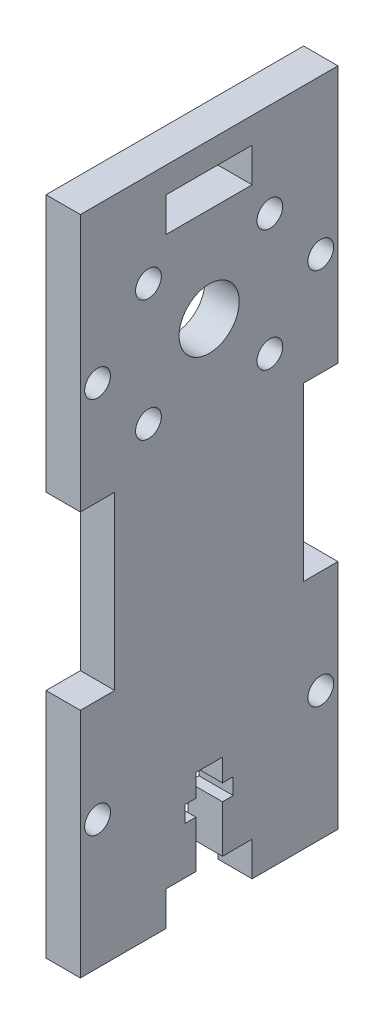
SolidWorks part; units mm, degrees
ref_plane "Front Plane" through (0, 0, 0) normal (0, 0, 1) x (1, 0, 0)
ref_plane "Top Plane" through (0, 0, 0) normal (0, 1, 0) x (1, 0, 0)
ref_plane "Right Plane" through (0, 0, 0) normal (1, 0, 0) x (0, 0, -1)
sketch "Sketch1" plane through (0, 0, 0) normal (1, 0, 0) x (0, 0, -1)
  line L0 (20, 74) -> (30, 74)
  line L1 (0, 0) -> (10, 0)
  line L2 (0, 0) -> (0, 74)
  line L3 (0, 74) -> (10, 74)
  line L4 (30, 0) -> (30, 74)
  line L6 (10, 74) -> (10, 70)
  line L7 (10, 70) -> (20, 70)
  line L8 (20, 74) -> (20, 70)
  line L10 (10, 0) -> (10, 4)
  line L11 (10, 4) -> (20, 4)
  line L12 (20, 0) -> (20, 4)
  line L13 (20, 0) -> (30, 0)
  line L14 (2, 74) -> (2, 0) construction
  line L15 (28, 74) -> (28, 0) construction
  line L16 (0, 37) -> (30, 37) construction
  line L18 (0, 47) -> (4, 47)
  line L19 (0, 47) -> (0, 27)
  line L20 (0, 27) -> (4, 27)
  line L21 (4, 47) -> (4, 27)
  line L22 (30, 27) -> (26, 27)
  line L23 (30, 27) -> (30, 47)
  line L24 (30, 47) -> (26, 47)
  line L25 (26, 27) -> (26, 47)
  circle A0 centre (2, 59) radius 1.5
  circle A1 centre (2, 15) radius 1.5
  circle A2 centre (28, 59) radius 1.5
  circle A3 centre (28, 15) radius 1.5
  dimension "D10" = 3
  dimension "D11" = 3
  dimension "D15" = 3
  dimension "D16" = 3
  dimension "D18" = 15
  dimension "D1" = 74
  dimension "D2" = 30
  dimension "D3" = 10
  dimension "D4" = 10
  dimension "D5" = 4
  dimension "D6" = 10
  dimension "D7" = 10
  dimension "D8" = 4
  dimension "D9" = 2
  dimension "D12" = 15
  dimension "D13" = 15
  dimension "D14" = 2
  dimension "D17" = 15
  dimension "D19" = 4
  dimension "D20" = 4
  dimension "D21" = 20
  dimension "D22" = 20
  dimension "D23" = 10
  dimension "D24" = 10
extrude "Boss-Extrude1" add sketch "Sketch1" along normal blind 4 contours L22 L25 L24 L4 L0 L8 L7 L6 L3 L2 L18 L21 L20 L1 L10 L11 L12 L13 A3 A2 A1 A0
sketch "Sketch2" plane through (4, 0, 0) normal (1, 0, 0) x (0, 0, -1)
  line L0 (20, 74) -> (30, 74) construction
  line L1 (0, 47) -> (0, 74) construction
  line L2 (15, 59) -> (5.4359, 59) construction
  line L3 (5.4359, 59) -> (15, 59) construction
  line L4 (15, 59) -> (3.0427, 70.9573) construction
  circle A0 centre (15, 59) radius 3.5
  circle A1 centre (7.9289, 66.0711) radius 1.5
  circle A2 centre (22.0711, 66.0711) radius 1.5
  circle A3 centre (22.0711, 51.9289) radius 1.5
  circle A4 centre (7.9289, 51.9289) radius 1.5
  point P19 (15, 59)
  dimension "D1" = 7
  dimension "D5" = 3
  dimension "D2" = 15
  dimension "D3" = 15
  dimension "D4" = 45
  dimension "D6" = 10
  dimension "D7" = 4
extrude "Cut-Extrude1" cut sketch "Sketch2" against normal blind 4
sketch "Sketch3" plane through (0, 74, 0) normal (0, 1, 0) x (1, 0, 0)
  line L1 (4, 0) -> (0, 0)
  line L2 (4, 0) -> (4, 30)
  line L3 (4, 30) -> (0, 30)
  line L4 (0, 0) -> (0, 30)
extrude "Boss-Extrude2" add sketch "Sketch3" along normal blind 3
sketch "Sketch5" plane through (4, 0, 0) normal (1, 0, 0) x (0, 0, -1)
  line L0 (15, 4) -> (15, 16.588) construction
  line L1 (10, 4) -> (20, 4) construction
  line L3 (13.45, 4) -> (16.55, 4)
  line L4 (13.45, 4) -> (13.45, 14)
  line L5 (13.45, 14) -> (16.55, 14)
  line L6 (16.55, 4) -> (16.55, 14)
  line L7 (12.2, 11.4) -> (17.8, 11.4)
  line L8 (12.2, 11.4) -> (12.2, 9.5)
  line L9 (12.2, 9.5) -> (17.8, 9.5)
  line L10 (17.8, 11.4) -> (17.8, 9.5)
  line M19 (10, 4) -> (20, 4)
  dimension "D1" = 10
  dimension "D2" = 1.55
  dimension "D3" = 1.55
  dimension "D4" = 1.25
  dimension "D5" = 1.25
  dimension "D6" = 1.9
  dimension "D7" = 5.5
extrude "Cut-Extrude2" cut sketch "Sketch5" against normal blind 10 contours L7 L0 L5 L4 | L9 L0 L7 L4 | L0 L9 L4 M19 | L0 L7 L6 L5 | L0 L9 L6 L7 | L0 L3 L6 L9 | L10 L7 L6 L9 | L8 L9 L4 L7
